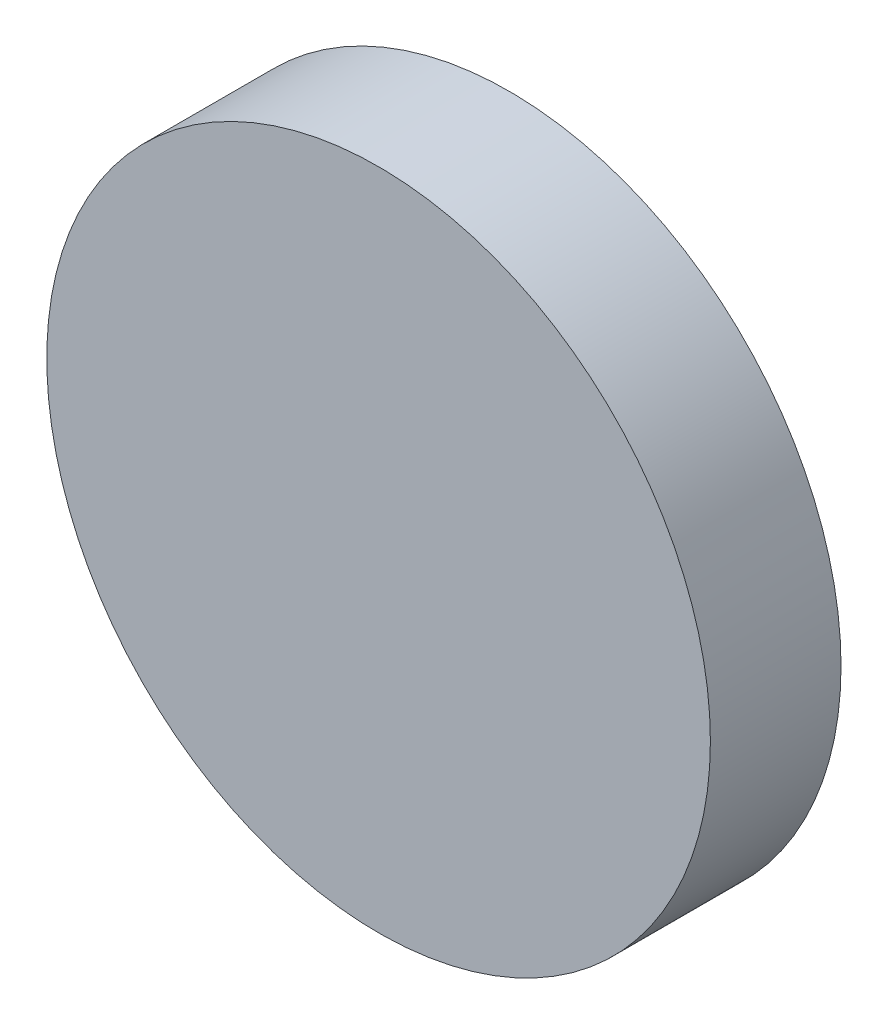
SolidWorks part; units mm, degrees
ref_plane "Front Plane" through (0, 0, 0) normal (0, 0, 1) x (1, 0, 0)
ref_plane "Top Plane" through (0, 0, 0) normal (0, 1, 0) x (1, 0, 0)
ref_plane "Right Plane" through (0, 0, 0) normal (1, 0, 0) x (0, 0, -1)
sketch "Sketch1" plane through (0, 0, 0) normal (0, 0, 1) x (1, 0, 0)
  circle A0 centre (-19.8787, 7.2563) radius 76.2
  dimension "D1" = 152.4
extrude "Boss-Extrude1" add sketch "Sketch1" along normal blind 30
